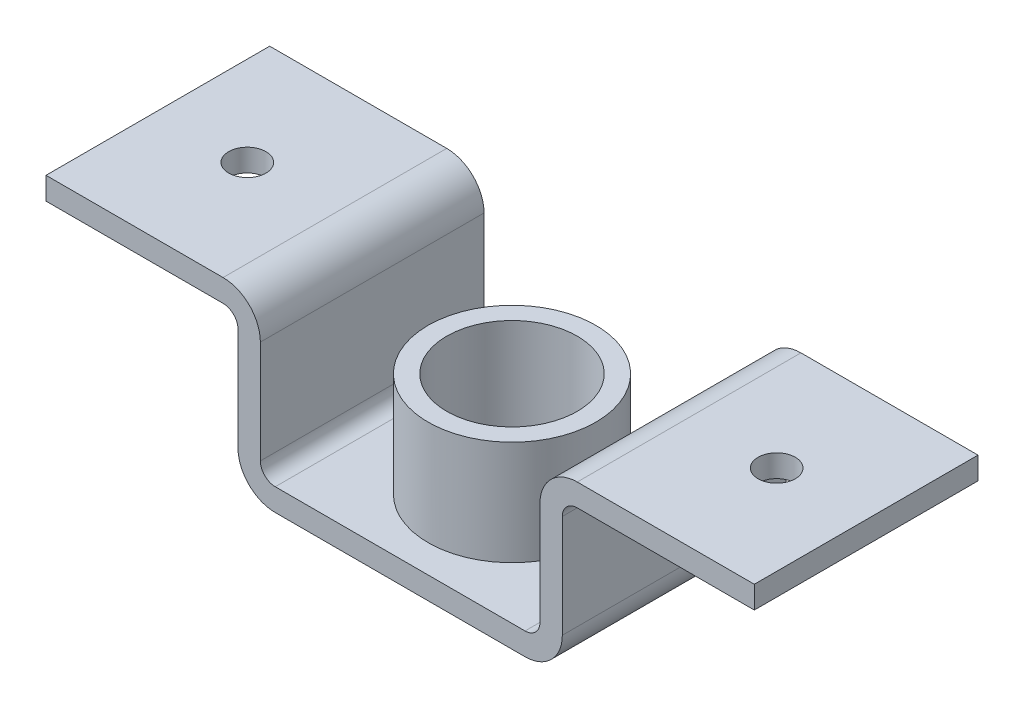
SolidWorks part; units mm, degrees
ref_plane "Front Plane" through (0, 0, 0) normal (0, 0, 1) x (1, 0, 0)
ref_plane "Top Plane" through (0, 0, 0) normal (0, 1, 0) x (1, 0, 0)
ref_plane "Right Plane" through (0, 0, 0) normal (1, 0, 0) x (0, 0, -1)
sketch "Sketch1" plane through (0, 0, 0) normal (0, 0, 1) x (1, 0, 0)
  line L0 (-536.9565, 0) -> (481.8841, 0) construction
  line L1 (0, 438.285) -> (0, -488.7681) construction
  line L2 (-475, 33.6039) -> (-217.5, 33.6039)
  line L3 (-217.5, 33.6039) -> (-217.5, -124.3961)
  line L4 (-475, 63.6039) -> (-187.5, 63.6039)
  line L5 (-187.5, 63.6039) -> (-187.5, -124.3961)
  line L6 (-167.5, -144.3961) -> (167.5, -144.3961)
  line L7 (187.5, -124.3961) -> (187.5, 63.6039)
  line L8 (187.5, 63.6039) -> (475, 63.6039)
  line L9 (-167.5, -174.3961) -> (167.5, -174.3961)
  line L10 (217.5, -124.3961) -> (217.5, 33.6039)
  line L11 (217.5, 33.6039) -> (475, 33.6039)
  line L12 (-475, 63.6039) -> (-475, 33.6039)
  line L13 (475, 63.6039) -> (475, 33.6039)
  arc A0 (167.5, -144.3961) -> (187.5, -124.3961) centre (167.5, -124.3961) ccw
  arc A1 (-187.5, -124.3961) -> (-167.5, -144.3961) centre (-167.5, -124.3961) ccw
  arc A2 (-217.5, -124.3961) -> (-167.5, -174.3961) centre (-167.5, -124.3961) ccw
  arc A3 (167.5, -174.3961) -> (217.5, -124.3961) centre (167.5, -124.3961) ccw
  point P14 (187.5, -144.3961)
  point P17 (-187.5, -144.3961)
  dimension "D2" = 20
  dimension "D10" = 50
  dimension "D1" = 950
  dimension "D3" = 238
  dimension "D4" = 375
  dimension "D5" = 475
  dimension "D6" = 475
  dimension "D7" = 187.5
  dimension "D8" = 187.5
  dimension "D9" = 30
extrude "Boss-Extrude1" add sketch "Sketch1" along normal mid plane 300
sketch "Sketch2" plane through (0, -144.3961, 0) normal (0, 1, 0) x (1, 0, 0)
  circle A0 centre (0, 0) radius 112.5
  circle A1 centre (0, 0) radius 87.5
  dimension "D1" = 225
  dimension "D2" = 175
extrude "Boss-Extrude2" add sketch "Sketch2" along normal blind 140
sketch "Sketch3" plane through (0, -144.3961, 0) normal (0, 1, 0) x (1, 0, 0)
  circle A0 centre (0, 0) radius 37.5
  dimension "D1" = 75
extrude "Cut-Extrude1" cut sketch "Sketch3" against normal blind 139
sketch "Sketch4" plane through (0, 63.6039, 0) normal (0, 1, 0) x (1, 0, 0)
  line L0 (-187.5, -150) -> (-475, -150) construction
  line L1 (-475, -150) -> (-475, 150) construction
  line L2 (475, -150) -> (475, 150) construction
  circle A0 centre (-355, 0) radius 25
  circle A1 centre (355, 0) radius 25
  dimension "D5" = 50
  dimension "D2" = 150
  dimension "D3" = 120
  dimension "D4" = 120
  dimension "D1" = 2
extrude "Cut-Extrude2" cut sketch "Sketch4" against normal blind 139
fillet "Fillet1" radius 50 2 edges at (187.5, 63.6039, 0) (-187.5, 63.6039, 0)
fillet "Fillet2" radius 20 2 edges at (217.5, 33.6039, 0) (-217.5, 33.6039, 0)
